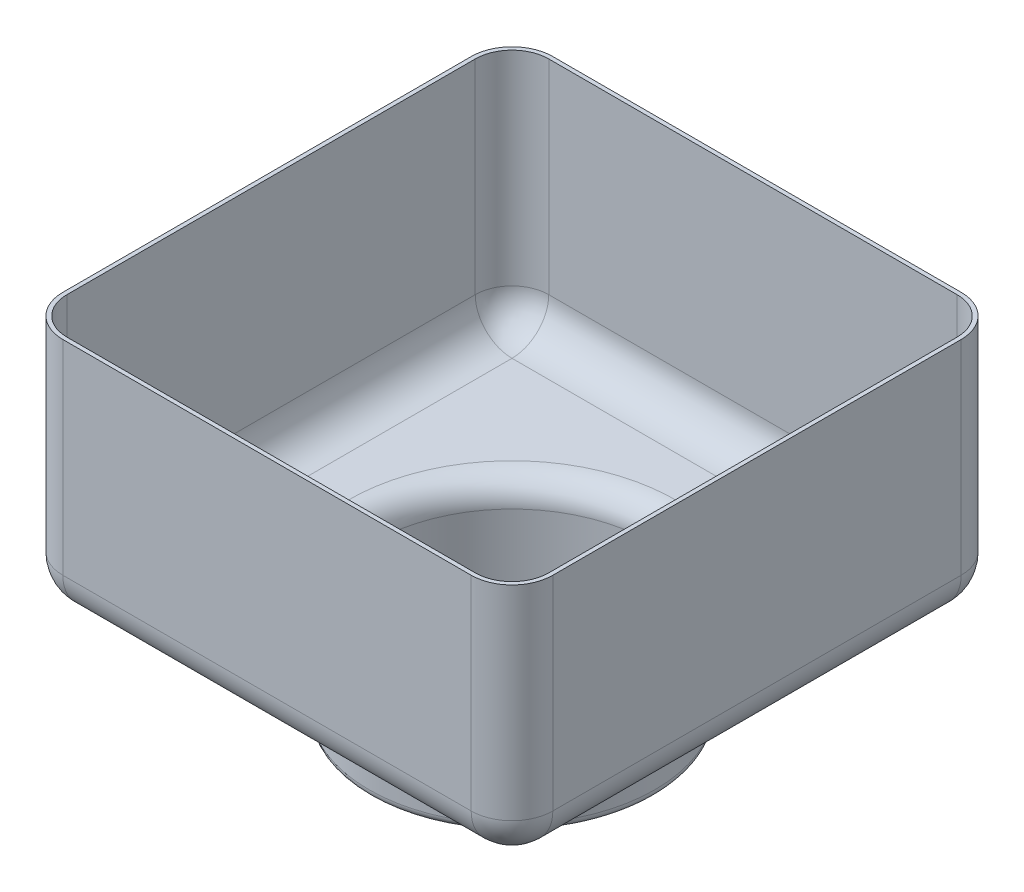
SolidWorks part; units mm, degrees
material "PS HI"
ref_plane "Front Plane" through (0, 0, 0) normal (0, 0, 1) x (1, 0, 0)
ref_plane "Top Plane" through (0, 0, 0) normal (0, 1, 0) x (1, 0, 0)
ref_plane "Right Plane" through (0, 0, 0) normal (1, 0, 0) x (0, 0, -1)
sketch "Sketch1" plane through (0, 0, 0) normal (0, 1, 0) x (1, 0, 0)
  line L1 (-107.3493, 55.074) -> (12.6507, 55.074)
  line L2 (-107.3493, 55.074) -> (-107.3493, -64.926)
  line L3 (-107.3493, -64.926) -> (12.6507, -64.926)
  line L4 (12.6507, 55.074) -> (12.6507, -64.926)
  circle A0 centre (-47.3493, -4.926) radius 35
  circle A1 centre (-47.3493, -4.926) radius 25
  dimension "D3" = 70
  dimension "D5" = 60
  dimension "D6" = 50
  dimension "D1" = 120
  dimension "D2" = 120
  dimension "D4" = 60
extrude "Boss-Extrude1" add sketch "Sketch1" along normal blind 25 contours A0 A1 | A1
sketch "Sketch2" plane through (0, 25, 0) normal (0, 1, 0) x (1, 0, 0)
  line L1 (-97.3493, 55.074) -> (2.6507, 55.074)
  line L2 (-107.3493, 45.074) -> (-107.3493, -54.926)
  line L3 (-97.3493, -64.926) -> (2.6507, -64.926)
  line L4 (12.6507, 45.074) -> (12.6507, -54.926)
  circle A0 centre (-47.3493, -4.926) radius 35 construction
  arc A1 (-97.3493, 55.074) -> (-107.3493, 45.074) centre (-97.3493, 45.074) ccw
  arc A2 (2.6507, 55.074) -> (12.6507, 45.074) centre (2.6507, 45.074) cw
  arc A3 (-107.3493, -54.926) -> (-97.3493, -64.926) centre (-97.3493, -54.926) ccw
  arc A4 (2.6507, -64.926) -> (12.6507, -54.926) centre (2.6507, -54.926) ccw
  point P8 (-107.3493, 55.074)
  point P13 (-107.3493, -64.926)
  point P16 (12.6507, -64.926)
  dimension "D3" = 60
  dimension "D4" = 60
  dimension "D5" = 10
  dimension "D6" = 10
  dimension "D7" = 10
  dimension "D1" = 120
  dimension "D2" = 120
extrude "Boss-Extrude2" add sketch "Sketch2" along normal blind 60
fillet "Fillet2" radius 10 8 edges at (9.7218, 25, -52.145) (9.7218, 25, 61.9971) (-47.3493, 25, 64.926) (-104.4203, 25, 61.9971) (-104.4203, 25, -52.145) (-107.3493, 25, 4.926) (12.6507, 25, 4.926) (-47.3493, 25, -55.074)
fillet "Fillet3" radius 5 1 edges at (-47.3493, 25, 39.926)
fillet "Fillet4" radius 2 1 edges at (-47.3493, 0, 39.926)
shell "Shell1" thickness 1
